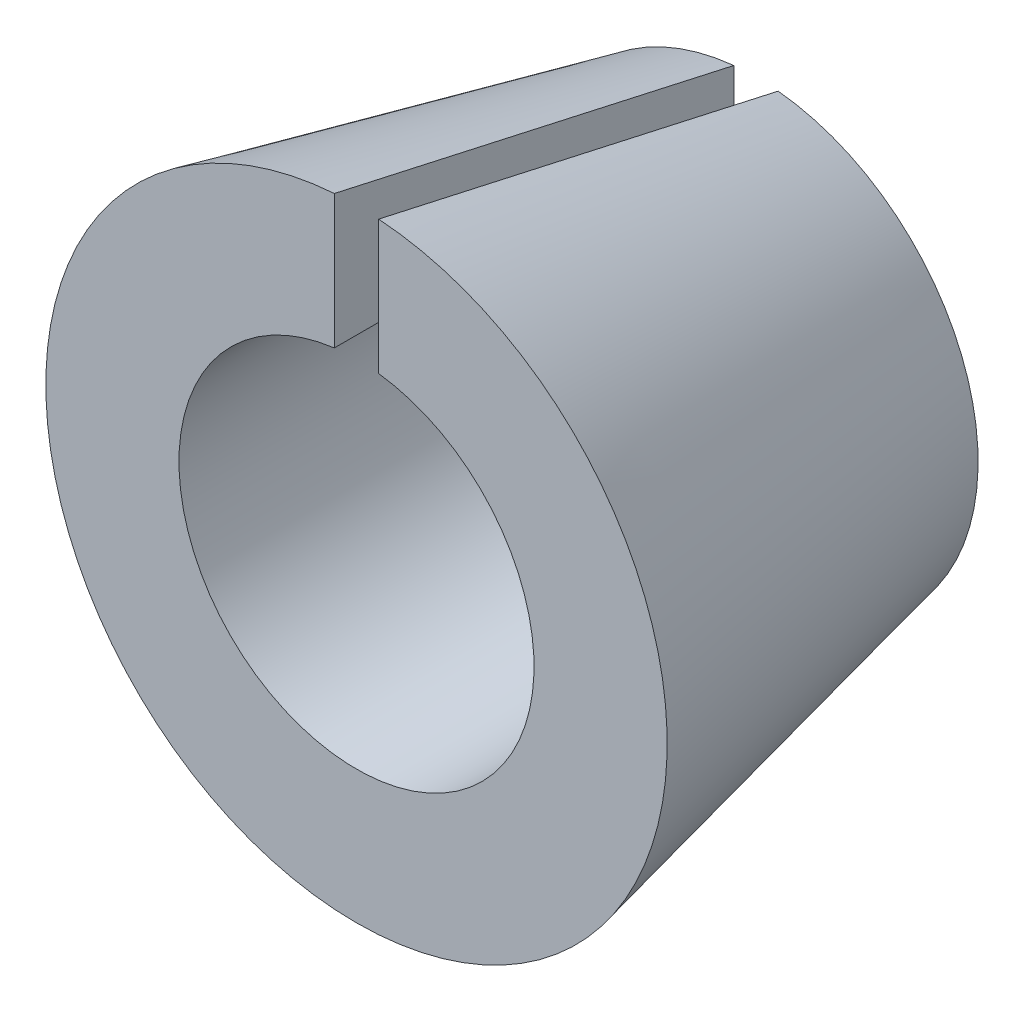
SolidWorks part; units mm, degrees
ref_plane "Face" through (0, 0, 0) normal (0, 0, 1) x (1, 0, 0)
ref_plane "Dessus" through (0, 0, 0) normal (0, 1, 0) x (1, 0, 0)
ref_plane "Droite" through (0, 0, 0) normal (1, 0, 0) x (0, 0, -1)
sketch "Esquisse1" plane through (0, 0, 0) normal (0, 0, 1) x (1, 0, 0)
  circle A0 centre (0, 0) radius 7
  dimension "D1" = 14
extrude "Base-Extrusion" add sketch "Esquisse1" against normal blind 9 draft 12.5
sketch "Esquisse5" plane through (0, 0, 0) normal (0, 0, 1) x (1, 0, 0)
  line L1 (-0.5, 7.5996) -> (0.5, 7.5996)
  line L2 (-0.5, 7.5996) -> (-0.5, 3.9686)
  line L4 (0.5, 7.5996) -> (0.5, 3.9686)
  arc A0 (-0.5, 3.9686) -> (0.5, 3.9686) centre (0, 0) ccw
  dimension "D3" = 4
  dimension "D1" = 0.5
  dimension "D2" = 1
extrude "Enlèv. mat.-Extru.2" cut sketch "Esquisse5" against normal through all
